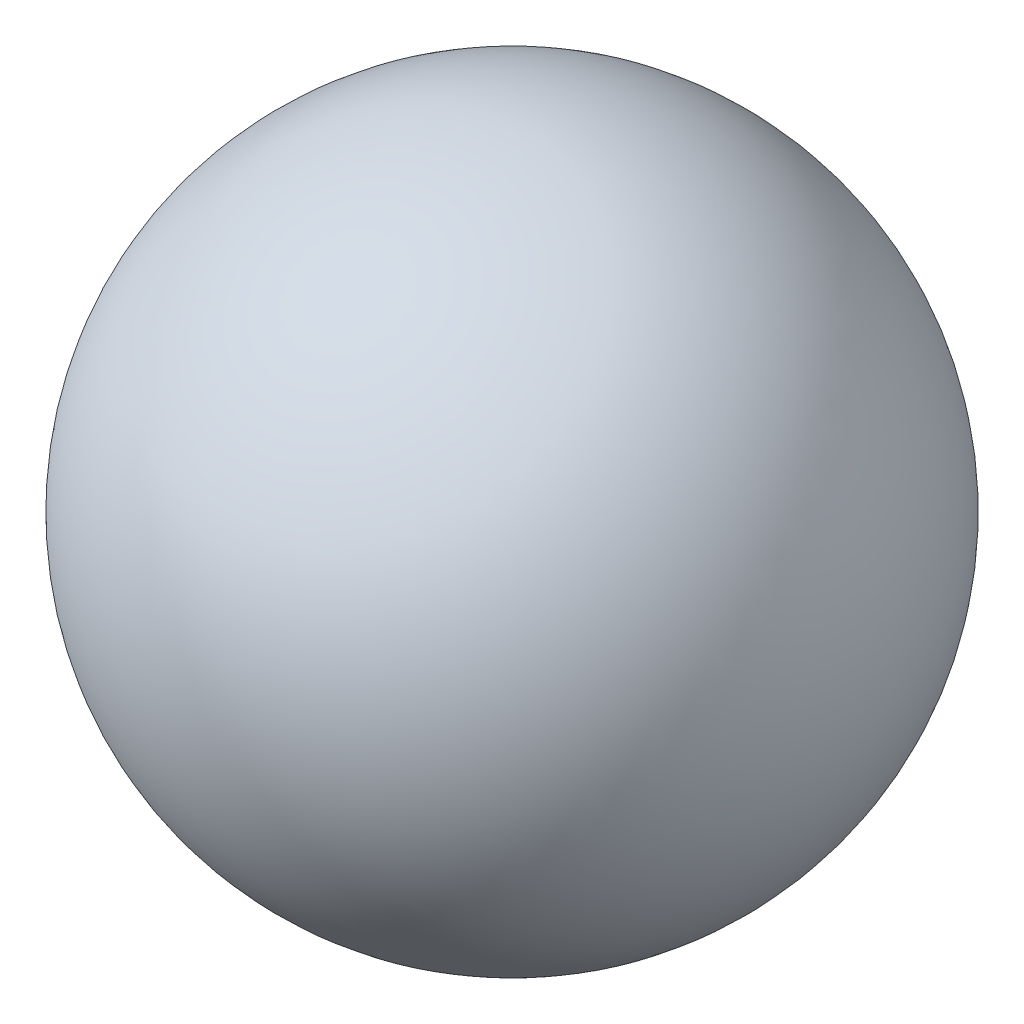
SolidWorks part; units mm, degrees
ref_plane "Front Plane" through (0, 0, 0) normal (0, 0, 1) x (1, 0, 0)
ref_plane "Top Plane" through (0, 0, 0) normal (0, 1, 0) x (1, 0, 0)
ref_plane "Right Plane" through (0, 0, 0) normal (1, 0, 0) x (0, 0, -1)
sketch "Sketch1" plane through (0, 0, 0) normal (0, 0, 1) x (1, 0, 0)
  line L4 (0, 12.7) -> (0, -12.7) construction
  line L5 (0, 12.7) -> (0, -12.7)
  arc A1 (0, 12.7) -> (0, -12.7) centre (0, 0) ccw
  point P2 (0, 0)
  dimension "D1" = 12.7
revolve "Revolve2" add sketch "Sketch1" angle 360 about L4
